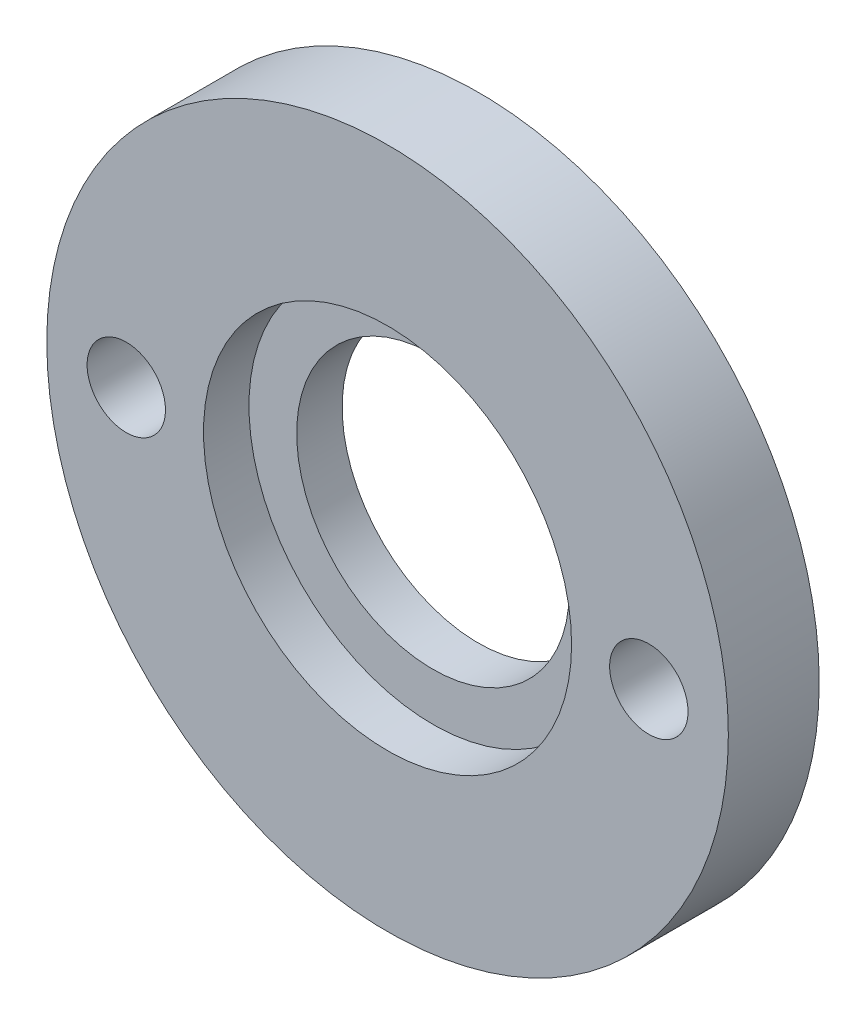
SolidWorks part; units mm, degrees
material "ABS"
ref_plane "Front Plane" through (0, 0, 0) normal (0, 0, 1) x (1, 0, 0)
ref_plane "Top Plane" through (0, 0, 0) normal (0, 1, 0) x (1, 0, 0)
ref_plane "Right Plane" through (0, 0, 0) normal (1, 0, 0) x (0, 0, -1)
sketch "Sketch1" plane through (0, 0, 0) normal (0, 0, 1) x (1, 0, 0)
  line L0 (0, 15) -> (0, -15) construction
  circle A0 centre (0, 0) radius 6
  circle A1 centre (0, 0) radius 15
  circle A2 centre (0, 0) radius 8 construction
  circle A5 centre (-11.5, 0) radius 1.725
  circle A6 centre (11.5, 0) radius 1.725
  dimension "D1" = 12
  dimension "D2" = 30
  dimension "D3" = 16
  dimension "D4" = 3.45
  dimension "D5" = 11.5
extrude "Boss-Extrude1" add sketch "Sketch1" along normal blind 4
sketch "Sketch2" plane through (0, 0, 4) normal (0, 0, 1) x (1, 0, 0)
  circle A0 centre (0, 0) radius 8.1
  circle A4 centre (0, 0) radius 6 construction
  circle A5 centre (0, 0) radius 6
  dimension "D1" = 16.2
extrude "Cut-Extrude1" cut sketch "Sketch2" against normal blind 2
equation "\"D4@Sketch1\"=3+\"print_free@Parameters@Parameters.SLDPRT\""
equation "\"D1@Sketch2\"=16.00mm+\"print_fit@Parameters@Parameters.SLDPRT\""
